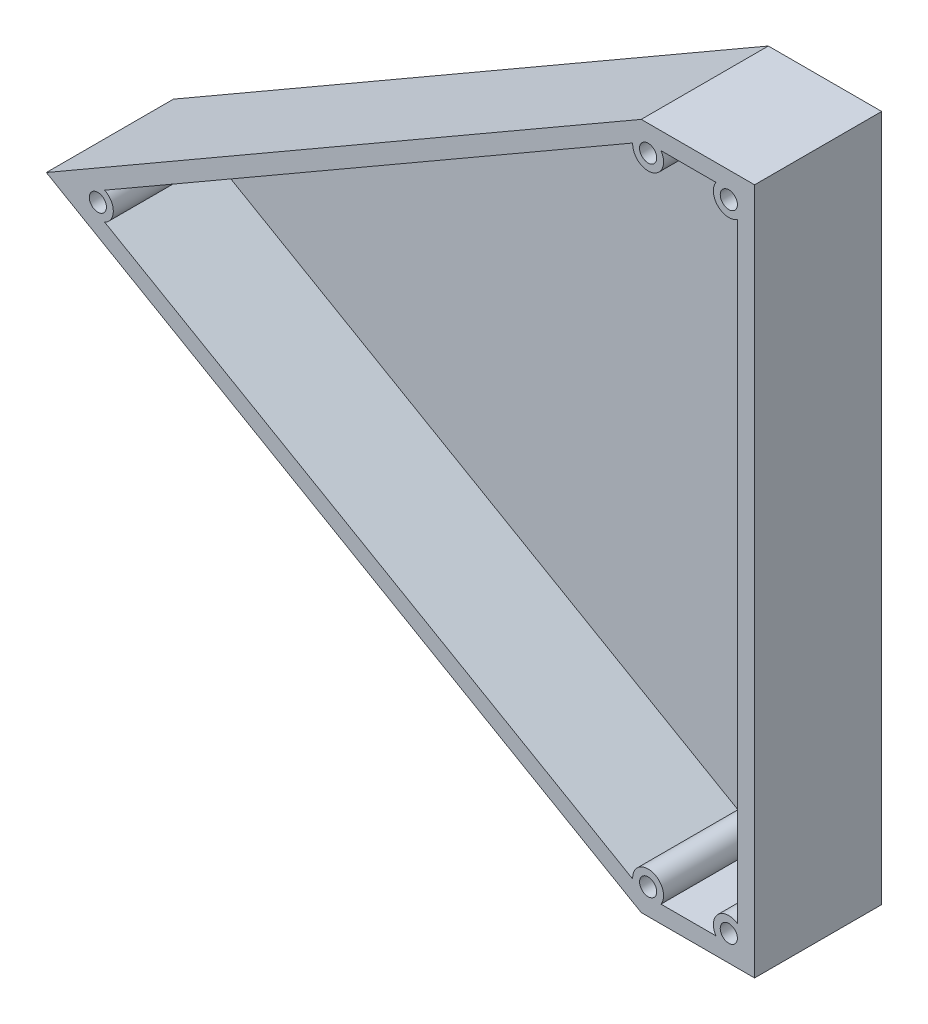
SolidWorks part; units mm, degrees
ref_plane "Front Plane" through (0, 0, 0) normal (0, 0, 1) x (1, 0, 0)
ref_plane "Top Plane" through (0, 0, 0) normal (0, 1, 0) x (1, 0, 0)
ref_plane "Right Plane" through (0, 0, 0) normal (1, 0, 0) x (0, 0, -1)
sketch "Sketch1" plane through (0, 0, 0) normal (0, 0, 1) x (1, 0, 0)
  line L0 (2.5, 0) -> (-30.5, 0)
  line L1 (2.5, 0) -> (-30.5, 0)
  line L2 (2.5, 0) -> (2.5, -200)
  line L3 (2.5, -200) -> (-30.5, -200)
  line L5 (-203.7051, -100) -> (-30.5, 0)
  line L6 (2.5, -200) -> (-30.5, -200) construction
  line L7 (-30.5, -200) -> (-203.7051, -100)
  dimension "D1" = 60
  dimension "D2" = 60
  dimension "D3" = 200
  dimension "D4" = 188.4551
  dimension "D5" = 200
  dimension "D6" = 0
extrude "Boss-Extrude1" add sketch "Sketch1" along normal blind 5 contours L7 L3 L2 L0 L5
sketch "Sketch2" plane through (0, 0, 5) normal (0, 0, 1) x (1, 0, 0)
  line L2 (-8.7417, -5) -> (-24.7487, -5)
  line L3 (-2.5, -100) -> (-136.8791, -100) construction
  line L4 (-2.5, -188.7583) -> (-2.5, -11.2417)
  line L5 (-203.7051, -100) -> (-30.5, -200)
  line L6 (-30.5, -200) -> (2.5, -200)
  line L7 (2.5, -200) -> (2.5, 0)
  line L8 (2.5, 0) -> (-30.5, 0)
  line L9 (-30.5, 0) -> (-203.7051, -100)
  line L10 (-203.7051, -100) -> (-30.5, -200)
  line L11 (-30.5, -200) -> (2.5, -200)
  line L12 (2.5, -200) -> (2.5, 0)
  line L13 (2.5, 0) -> (-30.5, 0)
  line L14 (-30.5, 0) -> (-203.7051, -100)
  line L15 (-24.7487, -195) -> (-8.7417, -195)
  line L16 (-186.7147, -95.9641) -> (-32.9808, -7.2058)
  line L17 (-186.7147, -104.0359) -> (-32.9808, -192.7942)
  circle A0 centre (-188.7051, -100) radius 2.5
  circle A1 centre (-5, -192.5) radius 2.5
  arc A2 (-186.7147, -104.0359) -> (-186.7147, -95.9641) centre (-188.7051, -100) ccw
  arc A3 (-2.5, -188.7583) -> (-8.7417, -195) centre (-5, -192.5) ccw
  circle A4 centre (-5, -7.5) radius 2.5
  arc A5 (-2.5, -11.2417) -> (-8.7417, -5) centre (-5, -7.5) cw
  circle A6 centre (-28.4904, -192.5) radius 2.5
  arc A7 (-24.7487, -195) -> (-32.9808, -192.7942) centre (-28.4904, -192.5) ccw
  circle A8 centre (-28.4904, -7.5) radius 2.5
  arc A9 (-24.7487, -5) -> (-32.9808, -7.2058) centre (-28.4904, -7.5) cw
  dimension "D6" = 5
  dimension "D7" = 2.5
  dimension "D9" = 2
  dimension "D5" = 5
  dimension "D10" = 5
  dimension "D12" = 2.5
  dimension "D13" = 2
  dimension "D2" = 5
  dimension "D4" = 5
  dimension "D1" = 0
extrude "Boss-Extrude2" add sketch "Sketch2" along normal blind 32
